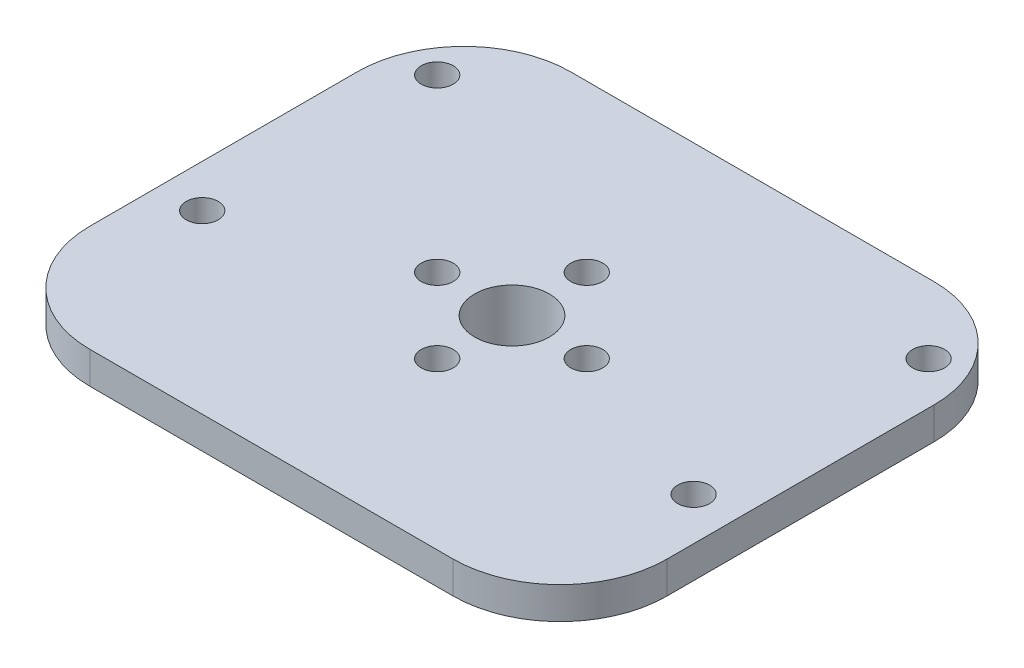
SolidWorks part; units mm, degrees
material "聚脂树脂"
ref_plane "前视基准面" through (0, 0, 0) normal (0, 0, 1) x (1, 0, 0)
ref_plane "上视基准面" through (0, 0, 0) normal (0, 1, 0) x (1, 0, 0)
ref_plane "右视基准面" through (0, 0, 0) normal (1, 0, 0) x (0, 0, -1)
other "Configuration Table"
sketch "草图1" plane through (0, 0, 0) normal (0, 1, 0) x (1, 0, 0)
  line L0 (0, 0) -> (36.9982, 0) construction
  line L1 (-27, -22.5) -> (27, -22.5)
  line L2 (-27, -22.5) -> (-27, 22.5)
  line L3 (-27, 22.5) -> (27, 22.5)
  line L4 (27, -22.5) -> (27, 22.5)
  line L5 (-27, -22.5) -> (27, 22.5) construction
  line L6 (-27, 22.5) -> (27, -22.5) construction
  line L7 (0, 0) -> (0, 22.4322) construction
  line L8 (0, 5) -> (42.8218, 5) construction
  circle A0 centre (0, 7) radius 1.5
  circle A1 centre (7, 0) radius 1.5
  circle A2 centre (0, 0) radius 3.5
  circle A3 centre (0, -7) radius 1.5
  circle A4 centre (-7, 0) radius 1.5
  circle A5 centre (23, 16) radius 1.5
  circle A9 centre (23, -6) radius 1.5
  circle A10 centre (-23, -6) radius 1.5
  circle A11 centre (-23, 16) radius 1.5
  point P0 (0, 0)
  dimension "D3" = 3
  dimension "D4" = 3
  dimension "D7" = 7
  dimension "D8" = 3
  dimension "D9" = 23
  dimension "D10" = 11
  dimension "D1" = 45
  dimension "D2" = 54
  dimension "D5" = 7
  dimension "D6" = 7
  dimension "D11" = 5
extrude "凸台-拉伸1" add sketch "草图1" along normal blind 3
sketch "草图2" plane through (0, 0, 0) normal (0, -1, 0) x (1, 0, 0)
  line L4 (27, -22.5) -> (27, 22.5)
  line L5 (27, 22.5) -> (-27, 22.5)
  line L6 (-27, 22.5) -> (-27, -22.5)
  line L7 (-27, -22.5) -> (27, -22.5)
  line L8 (27, -22.5) -> (27, 22.5)
  line L9 (27, 22.5) -> (-27, 22.5)
  line L10 (-27, 22.5) -> (-27, -22.5)
  line L11 (-27, -22.5) -> (27, -22.5)
  circle A0 centre (0, -7) radius 1.5 construction
  circle A1 centre (0, -7) radius 1.5
  circle A2 centre (-7, 0) radius 1.5 construction
  circle A3 centre (-7, 0) radius 1.5
  circle A4 centre (7, 0) radius 1.5 construction
  circle A5 centre (0, 7) radius 1.5 construction
  circle A6 centre (7, 0) radius 1.5
  circle A7 centre (0, 7) radius 1.5
  circle A8 centre (0, 0) radius 10
  circle A9 centre (0, 0) radius 3.5 construction
  circle A10 centre (0, 0) radius 3.5
  circle M6 centre (0, 7) radius 1.5
  circle M7 centre (7, 0) radius 1.5
  circle M12 centre (0, -7) radius 1.5
  circle M13 centre (0, 0) radius 3.5
  circle M14 centre (-7, 0) radius 1.5
  dimension "D2" = 20
  dimension "D1" = 0
extrude "凸台-拉伸2" add sketch "草图2" along normal blind 5 contours A8 M6 M13 M14 M12 M7
fillet "圆角1" radius 10 4 edges at (-27, 1.5, -22.5) (-27, 1.5, 22.5) (27, 1.5, -22.5) (27, 1.5, 22.5)
sketch "草图6" plane through (0, 0, 0) normal (0, -1, 0) x (1, 0, 0)
  circle A0 centre (0, 0) radius 10
  circle A1 centre (0, 0) radius 12
  dimension "D1" = 20
  dimension "D2" = 24
extrude "凸台-拉伸3" add sketch "草图6" along normal blind 5
sketch "草图7" plane through (0, -5, 0) normal (0, -1, 0) x (1, 0, 0)
  circle A0 centre (0, 0) radius 12
  circle A1 centre (0, 0) radius 10.5
  dimension "D1" = 24
  dimension "D2" = 21
extrude "凸台-拉伸4" add sketch "草图7" along normal blind 4
sketch "草图8" plane through (0, 0, 0) normal (0, -1, 0) x (1, 0, 0)
  circle A0 centre (0, 0) radius 20
  circle A1 centre (0, 0) radius 12
  dimension "D1" = 24
  dimension "D2" = 40
extrude "凸台-拉伸5" add sketch "草图8" along normal blind 2
